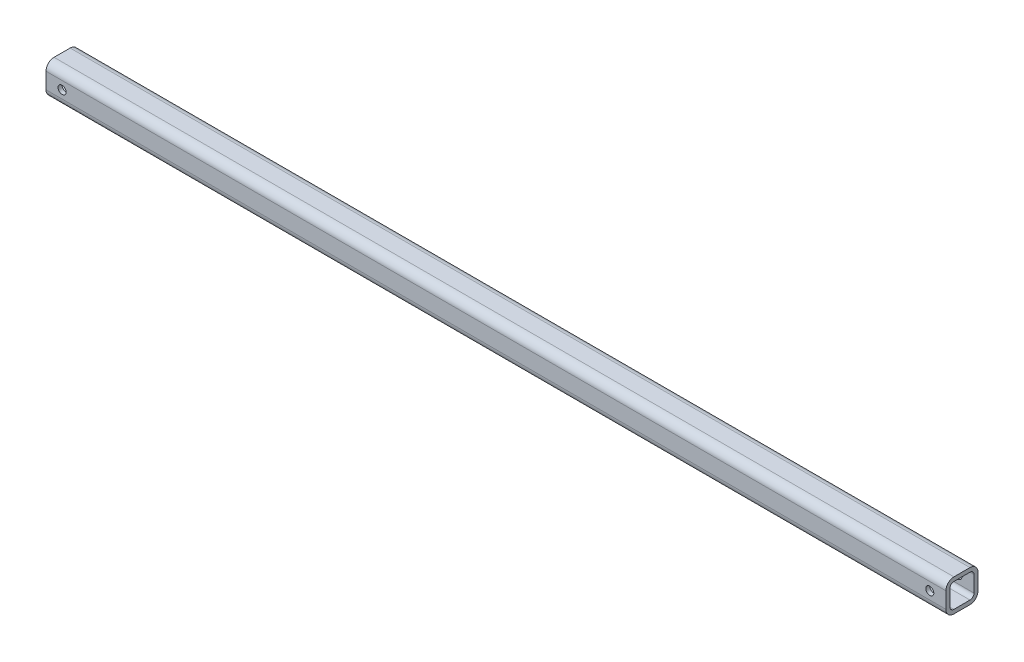
SolidWorks part; units mm, degrees
ref_plane "Front Plane" through (0, 0, 0) normal (0, 0, 1) x (1, 0, 0)
ref_plane "Top Plane" through (0, 0, 0) normal (0, 1, 0) x (1, 0, 0)
ref_plane "Right Plane" through (0, 0, 0) normal (1, 0, 0) x (0, 0, -1)
sketch "Sketch1" plane through (0, 0, 0) normal (0, 0, 1) x (1, 0, 0)
  line L0 (-741.5932, 0) -> (680.8068, 0)
  dimension "D1" = 1422.4
other "Structural Member1"
ref_plane "Plane1" through (-741.5932, 0, 0) normal (1, 0, 0) x (0, 1, 0)
sketch "Sketch11" plane through (-741.5932, 0, 0) normal (1, 0, 0) x (0, 1, 0)
  line L0 (-12.7, -19.05) -> (12.7, -19.05)
  line L1 (-19.05, -12.7) -> (-19.05, 12.7)
  line L2 (12.7, 19.05) -> (-12.7, 19.05)
  line L3 (19.05, 12.7) -> (19.05, -12.7)
  line L4 (-12.7, -25.4) -> (12.7, -25.4)
  line L5 (-25.4, -12.7) -> (-25.4, 12.7)
  line L6 (12.7, 25.4) -> (-12.7, 25.4)
  line L7 (25.4, 12.7) -> (25.4, -12.7)
  line L8 (0, 0) -> (19.05, 0) construction
  line L9 (0, 0) -> (0, 19.05) construction
  arc A0 (25.4, 12.7) -> (12.7, 25.4) centre (12.7, 12.7) ccw
  arc A1 (12.7, -25.4) -> (25.4, -12.7) centre (12.7, -12.7) ccw
  arc A2 (-25.4, -12.7) -> (-12.7, -25.4) centre (-12.7, -12.7) ccw
  arc A3 (-12.7, 25.4) -> (-25.4, 12.7) centre (-12.7, 12.7) ccw
  arc A4 (-12.7, 19.05) -> (-19.05, 12.7) centre (-12.7, 12.7) ccw
  arc A5 (19.05, 12.7) -> (12.7, 19.05) centre (12.7, 12.7) ccw
  arc A6 (12.7, -19.05) -> (19.05, -12.7) centre (12.7, -12.7) ccw
  arc A7 (-19.05, -12.7) -> (-12.7, -19.05) centre (-12.7, -12.7) ccw
  point P3 (0, 25.4)
  point P4 (25.4, 0)
  point P5 (0, -25.4)
  point P6 (-25.4, 0)
  point P7 (-25.4, 25.4)
  point P8 (-25.4, -25.4)
  point P33 (0, 0)
  point P35 (25.4, -25.4)
  point P36 (25.4, 25.4)
  point P37 (0, 0)
  dimension "D1" = 12.7
  dimension "Thickness" = 6.35
  dimension "V_leg" = 50.8
sketch "Sketch12" plane through (0, 0, 25.4) normal (0, 0, 1) x (1, 0, 0)
  line L0 (-741.5932, 0) -> (680.8068, 0) construction
  line L1 (-30.3932, 25.4) -> (-30.3932, -25.4) construction
  line L3 (680.8068, 25.4) -> (-741.5932, 25.4) construction
  line L4 (680.8068, -25.4) -> (-741.5932, -25.4) construction
  circle A0 centre (-716.1932, 0) radius 6.35
  circle A1 centre (655.4068, 0) radius 6.35
  dimension "D2" = 12.7
  dimension "D1" = 25.4
extrude "Cut-Extrude1" cut sketch "Sketch12" against normal through all
